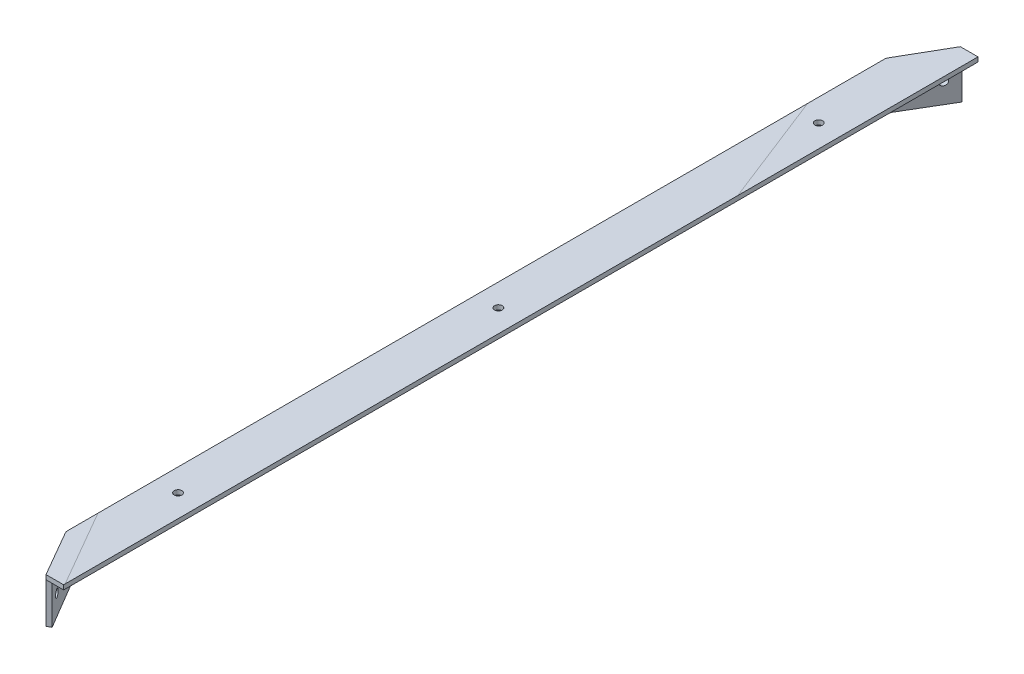
SolidWorks part; units mm, degrees
material "1.0116 (S235J2G3)"
ref_plane "Front Plane" through (0, 0, 0) normal (0, 0, 1) x (1, 0, 0)
ref_plane "Top Plane" through (0, 0, 0) normal (0, 1, 0) x (1, 0, 0)
ref_plane "Right Plane" through (0, 0, 0) normal (1, 0, 0) x (0, 0, -1)
sketch "Sketch1" plane through (0, 0, 0) normal (0, 0, 1) x (1, 0, 0)
  line L6 (0, 0) -> (0, 70)
  line L7 (0, 70) -> (70, 70)
  line L8 (70, 70) -> (70, 63)
  line L9 (70, 63) -> (7, 63)
  line L10 (7, 63) -> (7, 0)
  line L11 (7, 0) -> (0, 0)
  dimension "D1" = 70
  dimension "D2" = 70
  dimension "D3" = 7
  dimension "D4" = 7
extrude "Boss-Extrude1" add sketch "Sketch1" along normal blind 640
sketch "Sketch21" plane through (0, 0, 0) normal (0, 0, -1) x (-1, 0, 0)
  line L0 (0, 70) -> (-70, 70) construction
  line L1 (-70, 70) -> (-70, 0) construction
  line L2 (-70, 0) -> (0, 0) construction
  line L3 (0, 0) -> (0, 69.2595) construction
sketch "Sketch22" plane through (0, 70, 0) normal (0, 1, 0) x (1, 0, 0)
  line L0 (70, 0) -> (0, 0) construction
  line L1 (0, -55) -> (0, 55) construction
  circle A0 centre (35, 0) radius 6
  circle A1 centre (35, 500) radius 6
  circle A2 centre (35, -500) radius 6
  dimension "D1" = 12
  dimension "D2" = 12
  dimension "D3" = 12
  dimension "D4" = 500
  dimension "D5" = 500
  dimension "D6" = 35
  dimension "D7" = 35
extrude "Cut-Extrude4" cut sketch "Sketch22" against normal blind 10
sketch "Sketch23" plane through (0, 0, 0) normal (0, 1, 0) x (1, 0, 0)
  line L0 (0, -640) -> (42.5, -713.6122)
  line L1 (42.5, -713.6122) -> (48.5622, -710.1122)
  line L2 (48.5622, -710.1122) -> (7, -640)
  line L3 (7, -640) -> (0, -640)
  line L4 (0, -55) -> (0, 55) construction
  dimension "D1" = 7
  dimension "D2" = 210
  dimension "D3" = 85
extrude "Boss-Extrude2" add sketch "Sketch23" along normal blind 63
sketch "Sketch25" plane through (0, 63, 0) normal (0, 1, 0) x (1, 0, 0)
  line L0 (70, -640) -> (0, -640)
  line L1 (70, -640) -> (70, 0) construction
  line L2 (7, -640) -> (70, -640) construction
  line L3 (0, -640) -> (42.5, -713.6122) construction
  line L4 (0, -640) -> (42.5, -713.6122)
  line L5 (42.5, -713.6122) -> (48.5622, -710.1122) construction
  line L6 (42.5, -713.6122) -> (70, -713.6122)
  line L7 (70, -713.6122) -> (70, -640)
extrude "Boss-Extrude3" add sketch "Sketch25" along normal blind 7
sketch "Sketch26" plane through (-275.5567, 0, 163.3488) normal (0.8602, 0, -0.5099) x (-0.5099, 0, -0.8602)
  line L0 (-635.6125, 0) -> (-554.1071, 0) construction
  line L1 (-635.6125, 63) -> (-635.6125, 0) construction
  line L2 (-554.1071, 0) -> (-554.1071, 63) construction
  circle A0 centre (-614.3625, 31.5) radius 6
  circle A1 centre (-575.3671, 31.5) radius 6
  dimension "D1" = 12
  dimension "D2" = 12
  dimension "D3" = 31.5
  dimension "D4" = 31.5
  dimension "D5" = 21.25
  dimension "D6" = 21.26
extrude "Cut-Extrude5" cut sketch "Sketch26" against normal blind 7
mirror "Mirror1" about plane through (0, 0, 0) normal (0, 0, 1) of bodies 114 116
sketch "Sketch28" plane through (0, 70, 0) normal (0, 1, 0) x (1, 0, 0)
  line L0 (0, -590) -> (70, -711.2436)
  line L1 (0, -38.5) -> (0, 38.5) construction
  line L2 (70, -711.2436) -> (70, 338.6122)
  line L3 (70, 338.6122) -> (0, 517.6122)
  line L4 (0, 517.6122) -> (0, -590)
  line L5 (0, -640) -> (42.5, -713.6122) construction
  line L8 (70, -713.6122) -> (70, 713.6122) construction
  line L11 (42.5, 713.6122) -> (70, 713.6122) construction
  dimension "D1" = 25
  dimension "D2" = 375
  dimension "D3" = 196
split line "Split Line1"
fillet "Fillet1" radius 10 2 edges at (0, 35, 640) (0, 35, -640)
fillet "Fillet2" radius 10 2 edges at (7, 31.5, 640) (7, 31.5, -640)
